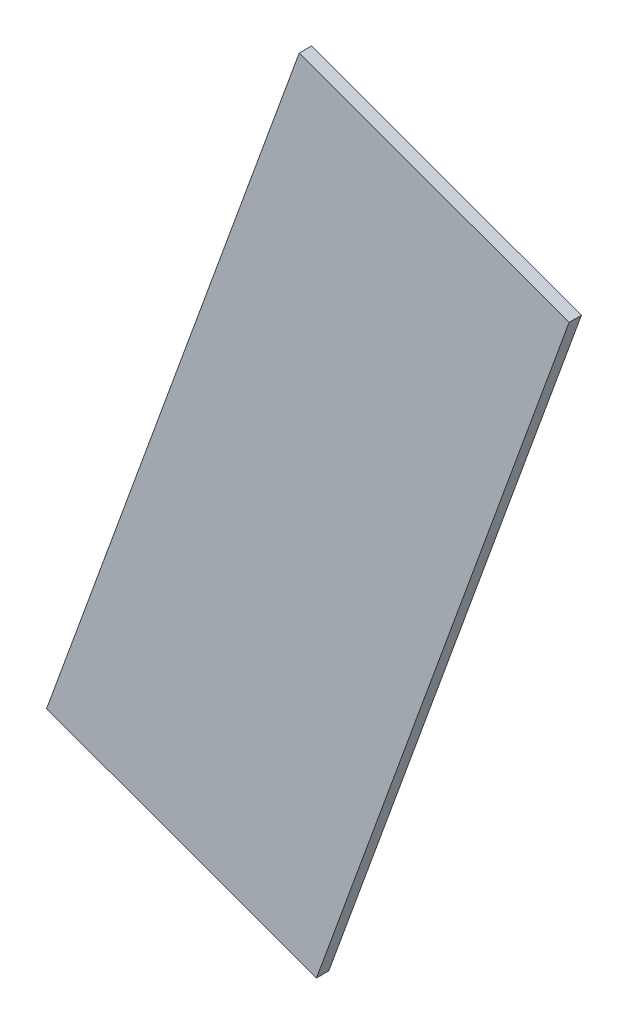
SolidWorks part; units mm, degrees
material "Thornel Mat VMA"
ref_plane "前视基准面" through (0, 0, 0) normal (0, 0, 1) x (1, 0, 0)
ref_plane "上视基准面" through (0, 0, 0) normal (0, 1, 0) x (1, 0, 0)
ref_plane "右视基准面" through (0, 0, 0) normal (1, 0, 0) x (0, 0, -1)
other "Configuration Table"
sketch "草图1" plane through (0, 0, 0) normal (0, 0, 1) x (1, 0, 0)
  line L0 (385.6022, 660.2252) -> (447.1658, 829.3699)
  line L3 (385.6022, 660.2252) -> (319.8237, 684.1666)
  line L4 (319.8237, 684.1666) -> (381.3873, 853.3113)
  line L7 (447.1658, 829.3699) -> (381.3873, 853.3113)
  line L9 (328.5815, 686.2999) -> (326.8714, 681.6014) construction
  dimension "D1" = 180
  dimension "D2" = 70
  dimension "D3" = 7.5
extrude "凸台-拉伸1" add sketch "草图1" along normal blind 3
